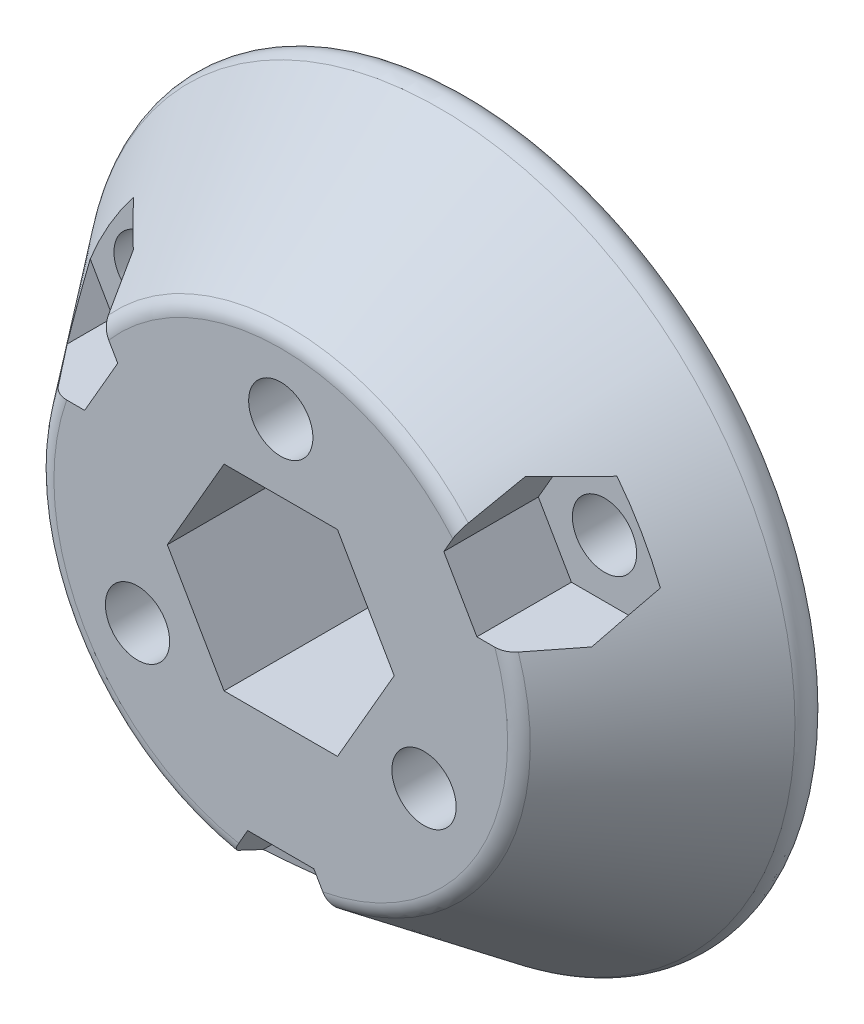
SolidWorks part; units mm, degrees
ref_plane "前视基准面" through (0, 0, 0) normal (0, 0, 1) x (1, 0, 0)
ref_plane "上视基准面" through (0, 0, 0) normal (0, 1, 0) x (1, 0, 0)
ref_plane "右视基准面" through (0, 0, 0) normal (1, 0, 0) x (0, 0, -1)
sketch "草图1" plane through (0, 0, 0) normal (0, 0, 1) x (1, 0, 0)
  circle A0 centre (0, 0) radius 20
  dimension "D1" = 40
ref_plane "基准面1" through (0, 0, 10) normal (0, 0, 1) x (1, 0, 0)
sketch "草图2" plane through (0, 0, 10) normal (0, 0, 1) x (1, 0, 0)
  circle A0 centre (0, 0) radius 12.5
  dimension "D1" = 25
loft "放样1" add profiles "草图1", "草图2"
fillet "圆角1" radius 1 2 edges at (12.5, 0, 10) (20, 0, 0)
sketch "草图3" plane through (0, 0, 0) normal (0, 0, -1) x (-1, 0, 0)
  line L0 (0, 0) -> (0, -14) construction
  line L1 (0, 0) -> (0, 8.75) construction
  circle A0 centre (0, 0) radius 14 construction
  circle A1 centre (0, -14) radius 1.7
  circle A2 centre (-12.1244, 7) radius 1.7
  circle A3 centre (12.1244, 7) radius 1.7
  circle A4 centre (0, 0) radius 8.75 construction
  circle A5 centre (0, 8.75) radius 1.7
  circle A6 centre (7.5777, -4.375) radius 1.7
  circle A7 centre (-7.5777, -4.375) radius 1.7
  point P11 (0, 0)
  point P19 (0, 0)
  dimension "D1" = 28
  dimension "D2" = 3.4
  dimension "D4" = 17.5
  dimension "D5" = 3.4
  dimension "D3" = 3
  dimension "D6" = 3
extrude "切除-拉伸1" cut sketch "草图3" against normal through all
sketch "草图5" plane through (0, 0, 0) normal (0, 0, -1) x (-1, 0, 0)
  line L0 (0, 0) -> (0, 10.45) construction
  line L1 (-3, 5.1962) -> (-6, 0)
  line L2 (-6, 0) -> (-3, -5.1962)
  line L3 (-3, -5.1962) -> (3, -5.1962)
  line L4 (3, -5.1962) -> (6, 0)
  line L5 (6, 0) -> (3, 5.1962)
  line L6 (3, 5.1962) -> (-3, 5.1962)
  circle A0 centre (0, 0) radius 5.1962 construction
  circle A1 centre (0, 0) radius 6 construction
  circle A2 centre (0, 8.75) radius 1.7 construction
  point P10 (0, 5.1962)
  dimension "D1" = 12
extrude "切除-拉伸2" cut sketch "草图5" against normal through all
sketch "草图6" plane through (0, 0, 0) normal (0, 0, -1) x (-1, 0, 0)
  circle A0 centre (-7.5777, -4.375) radius 3
  circle A1 centre (7.5777, -4.375) radius 3
  circle A2 centre (0, 8.75) radius 3
  dimension "D1" = 6
  dimension "D2" = 6
  dimension "D3" = 6
extrude "切除-拉伸3" cut sketch "草图6" against normal blind 5
sketch "草图7" plane through (0, 0, 10) normal (0, 0, 1) x (1, 0, 0)
  line L0 (-6, 0) -> (-3, 5.1962) construction
  line L7 (-15.6244, 7) -> (-13.8744, 3.9689)
  line L8 (-13.8744, 3.9689) -> (-10.3744, 3.9689)
  line L9 (-10.3744, 3.9689) -> (-8.6244, 7)
  line L10 (-8.6244, 7) -> (-10.3744, 10.0311)
  line L11 (-10.3744, 10.0311) -> (-13.8744, 10.0311)
  line L12 (-13.8744, 10.0311) -> (-15.6244, 7)
  line L13 (13.8744, 3.9689) -> (15.6244, 7)
  line L14 (15.6244, 7) -> (13.8744, 10.0311)
  line L15 (13.8744, 10.0311) -> (10.3744, 10.0311)
  line L16 (10.3744, 10.0311) -> (8.6244, 7)
  line L17 (8.6244, 7) -> (10.3744, 3.9689)
  line L18 (10.3744, 3.9689) -> (13.8744, 3.9689)
  line L19 (-1.75, -10.9689) -> (-3.5, -14)
  line L20 (-3.5, -14) -> (-1.75, -17.0311)
  line L21 (-1.75, -17.0311) -> (1.75, -17.0311)
  line L22 (1.75, -17.0311) -> (3.5, -14)
  line L23 (3.5, -14) -> (1.75, -10.9689)
  line L24 (1.75, -10.9689) -> (-1.75, -10.9689)
  line L25 (3, 5.1962) -> (6, 0) construction
  line L26 (3, -5.1962) -> (-3, -5.1962) construction
  circle A10 centre (-12.1244, 7) radius 3.0311 construction
  circle A11 centre (12.1244, 7) radius 3.0311 construction
  circle A12 centre (0, -14) radius 3.0311 construction
  arc A13 (-10.4652, 7.3702) -> (-11.6154, 5.378) centre (-12.1244, 7) ccw construction
  arc A14 (11.6154, 5.378) -> (10.4652, 7.3702) centre (12.1244, 7) ccw construction
  arc A15 (-1.1502, -12.7482) -> (1.1502, -12.7482) centre (0, -14) ccw construction
  dimension "D1" = 3.5
  dimension "D2" = 3.5
  dimension "D3" = 3.5
extrude "切除-拉伸4" cut sketch "草图7" against normal blind 5
